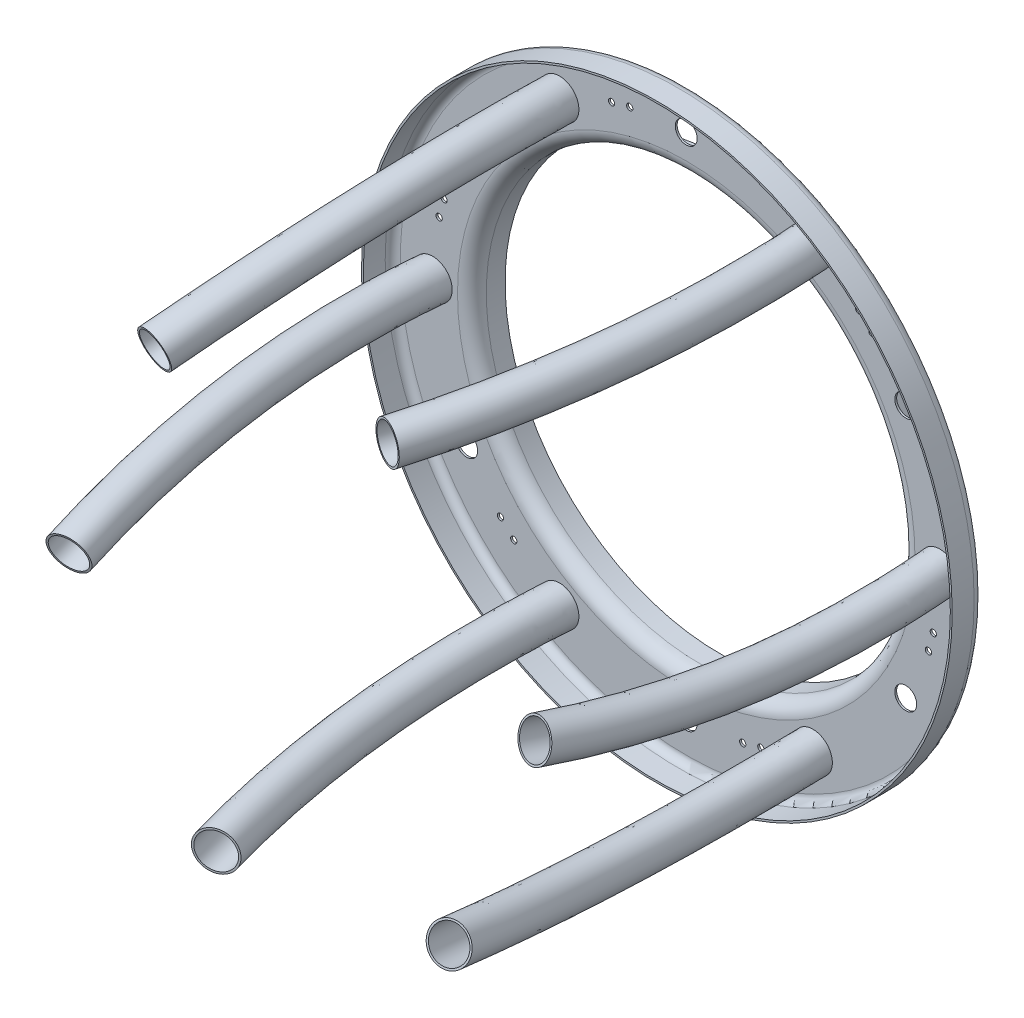
SolidWorks part; units mm, degrees
material "AISI 304"
ref_plane "Front Plane" through (0, 0, 0) normal (0, 0, 1) x (1, 0, 0)
ref_plane "Top Plane" through (0, 0, 0) normal (0, 1, 0) x (1, 0, 0)
ref_plane "Right Plane" through (0, 0, 0) normal (1, 0, 0) x (0, 0, -1)
sketch "Sketch1" plane through (0, 0, 0) normal (0, 1, 0) x (1, 0, 0)
  line L0 (0, 0) -> (0, 46.9497) construction
  line L1 (-34.55, 10) -> (-34.25, 10)
  line L2 (-34.25, 7) -> (-34.25, 10)
  line L3 (-47.2, 3.5) -> (-47.2, 0)
  line L4 (-46.9, 0) -> (-47.2, 0)
  line L5 (-46.9, 3.5) -> (-46.9, 0)
  line L7 (-45.7, 5) -> (-36.55, 5)
  line L9 (-36.55, 4.7) -> (-45.7, 4.7)
  line L11 (-34.55, 10) -> (-34.55, 7)
  arc A0 (-46.9, 3.5) -> (-45.7, 4.7) centre (-45.7, 3.5) cw
  arc A1 (-47.2, 3.5) -> (-45.7, 5) centre (-45.7, 3.5) cw
  arc A2 (-34.55, 7) -> (-36.55, 5) centre (-36.55, 7) cw
  arc A3 (-34.25, 7) -> (-36.55, 4.7) centre (-36.55, 7) cw
  dimension "D3" = 2
  dimension "D4" = 2.3
  dimension "D2" = 1.5
  dimension "D1" = 1.2
revolve "Revolve2" add sketch "Sketch1" angle 360 about L0
sketch "Sketch2" plane through (0, 0, -5) normal (0, 0, -1) x (-1, 0, 0)
  circle A1 centre (40.5, 0) radius 3
  circle A2 centre (35.074, 20.25) radius 1.75
  circle A4 centre (38.705, 11.9236) radius 0.5
  circle A5 centre (39.4813, 9.0263) radius 0.5
extrude "Cut-Extrude1" cut sketch "Sketch2" against normal blind 10
pattern_circular "CirPattern2" count 6 over 360 about axis through (0, 0, 0) along (0, 0, 1) of "Cut-Extrude1"
sketch "Sketch3" plane through (0, 0, -4.7) normal (0, 0, 1) x (1, 0, 0)
  circle A0 centre (20.25, 35.074) radius 3.1
  circle A1 centre (20.25, 35.074) radius 2.8
sketch "Sketch5" plane through (0, 0, 0) normal (0, 1, 0) x (1, 0, 0)
  line L0 (17.15, 4.7) -> (23.35, 4.7) construction
  arc A0 (20.25, 4.7) -> (13.6927, -56.7079) centre (-158.9014, -7.2238) cw
sweep "Sweep1" add profiles "Sketch3" path "Sketch5"
pattern_circular "CirPattern3" count 6 over 360 about axis through (0, 0, -4.7) along (0, 0, 1) of "Sweep1"
scale "Scale1" scale about centroid uniform scaling yes scale factor 1.4
scale "Scale2" scale about centroid uniform scaling yes scale factor 0.9
scale "Scale3" scale about centroid uniform scaling yes scale factor 0.9
scale "Scale4" scale about centroid uniform scaling yes scale factor 0.8
scale "Scale5" scale about centroid uniform scaling yes scale factor 1.1
scale "Scale6" scale about centroid uniform scaling yes scale factor 1.1
scale "Scale7" scale about centroid uniform scaling yes scale factor 1.1
scale "Scale8" scale about centroid uniform scaling yes scale factor 0.98
